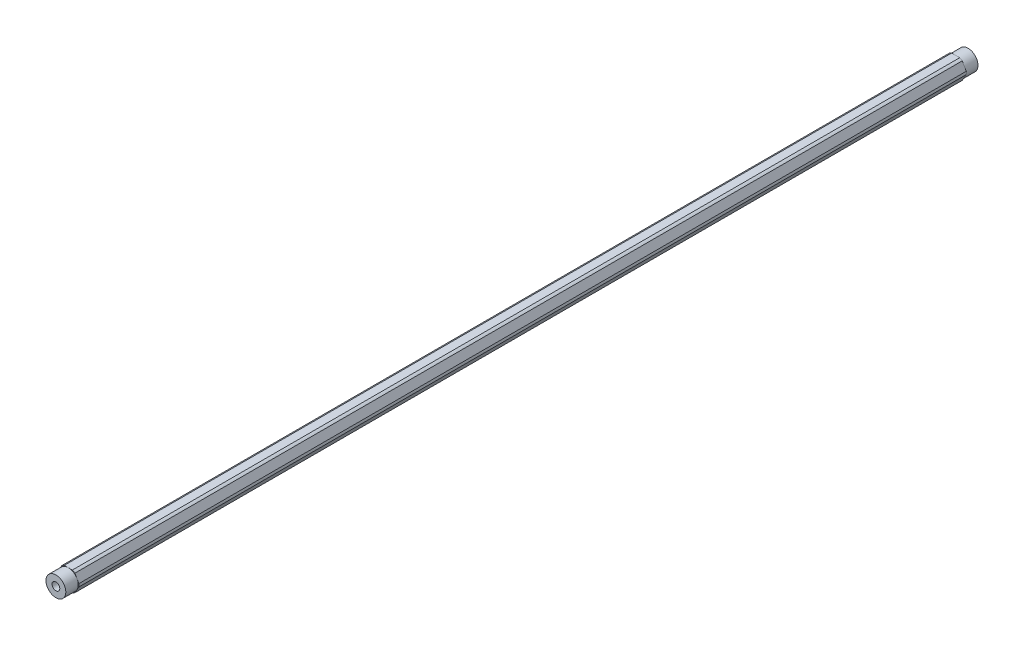
SolidWorks part; units mm, degrees
ref_plane "Front Plane" through (0, 0, 0) normal (0, 0, 1) x (1, 0, 0)
ref_plane "Top Plane" through (0, 0, 0) normal (0, 1, 0) x (1, 0, 0)
ref_plane "Right Plane" through (0, 0, 0) normal (1, 0, 0) x (0, 0, -1)
sketch "Sketch1" plane through (0, 0, 0) normal (0, 0, 1) x (1, 0, 0)
  line L1 (7.3323, 0) -> (3.6662, 6.35)
  line L2 (3.6662, 6.35) -> (-3.6662, 6.35)
  line L3 (-3.6662, 6.35) -> (-7.3323, 0)
  line L4 (-7.3323, 0) -> (-3.6662, -6.35)
  line L5 (-3.6662, -6.35) -> (3.6662, -6.35)
  line L6 (3.6662, -6.35) -> (7.3323, 0)
  circle A0 centre (0, 0) radius 6.35 construction
  dimension "D1" = 12.7
extrude "Boss-Extrude1" add sketch "Sketch1" along normal mid plane 584.2
sketch "Sketch3" plane through (0, 0, 292.1) normal (0, 0, 1) x (1, 0, 0)
  circle A0 centre (0, 0) radius 6.35
extrude "Cut-Extrude2" cut sketch "Sketch3" against normal blind 7.9502 flip side to cut
mirror "Mirror1" about plane through (0, 0, 0) normal (0, 0, 1) of "Cut-Extrude2"
sketch "Sketch4" plane through (0, 0, 292.1) normal (0, 0, 1) x (1, 0, 0)
  circle A0 centre (0, 0) radius 6.858
  dimension "D1" = 13.716
extrude "Cut-Extrude3" cut sketch "Sketch4" against normal through all flip side to cut
sketch "Sketch5" plane through (0, 0, 292.1) normal (0, 0, 1) x (1, 0, 0)
  circle A0 centre (0, 0) radius 2.4892
  dimension "D1" = 4.9784
extrude "Cut-Extrude4" cut sketch "Sketch5" against normal through all contours A0
